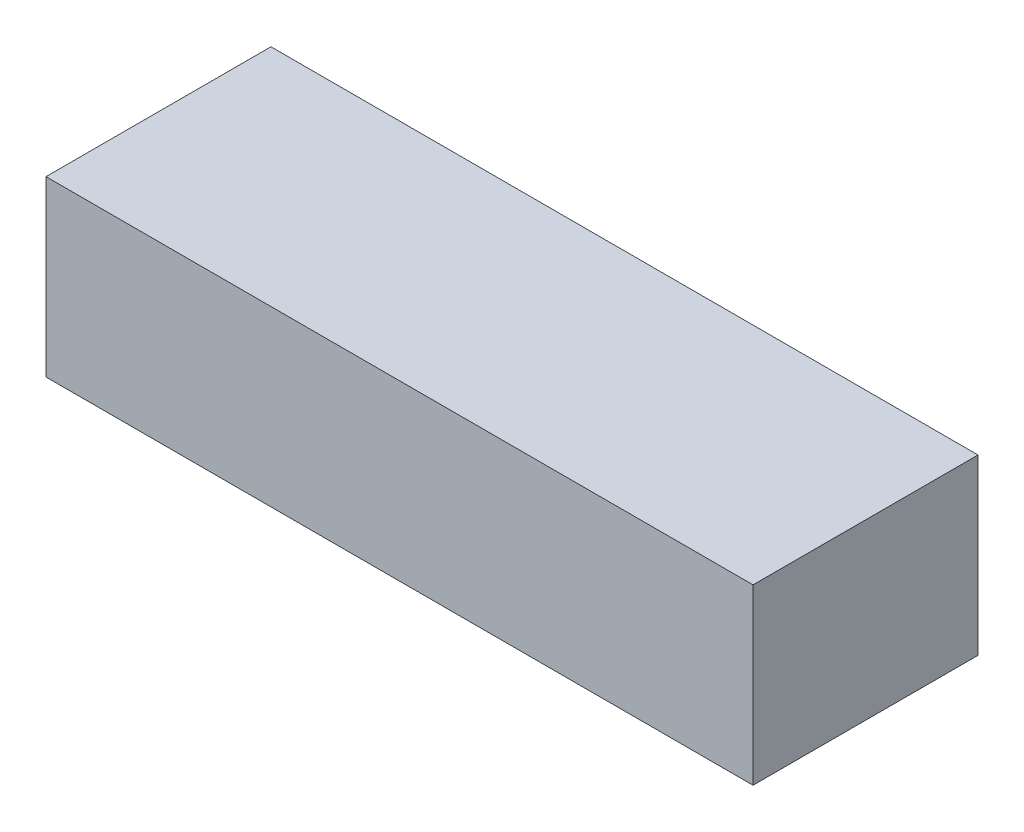
SolidWorks part; units mm, degrees
ref_plane "前视基准面" through (0, 0, 0) normal (0, 0, 1) x (1, 0, 0)
ref_plane "上视基准面" through (0, 0, 0) normal (0, 1, 0) x (1, 0, 0)
ref_plane "右视基准面" through (0, 0, 0) normal (1, 0, 0) x (0, 0, -1)
sketch "草图1" plane through (0, 0, 0) normal (0, 1, 0) x (1, 0, 0)
  line L1 (-55, 17.5) -> (55, 17.5)
  line L2 (-55, 17.5) -> (-55, -17.5)
  line L3 (-55, -17.5) -> (55, -17.5)
  line L4 (55, 17.5) -> (55, -17.5)
  line L5 (-55, 17.5) -> (55, -17.5) construction
  line L6 (-55, -17.5) -> (55, 17.5) construction
  point P0 (0, 0)
  dimension "D1" = 110
  dimension "D2" = 35
extrude "凸台-拉伸1" add sketch "草图1" along normal blind 27
